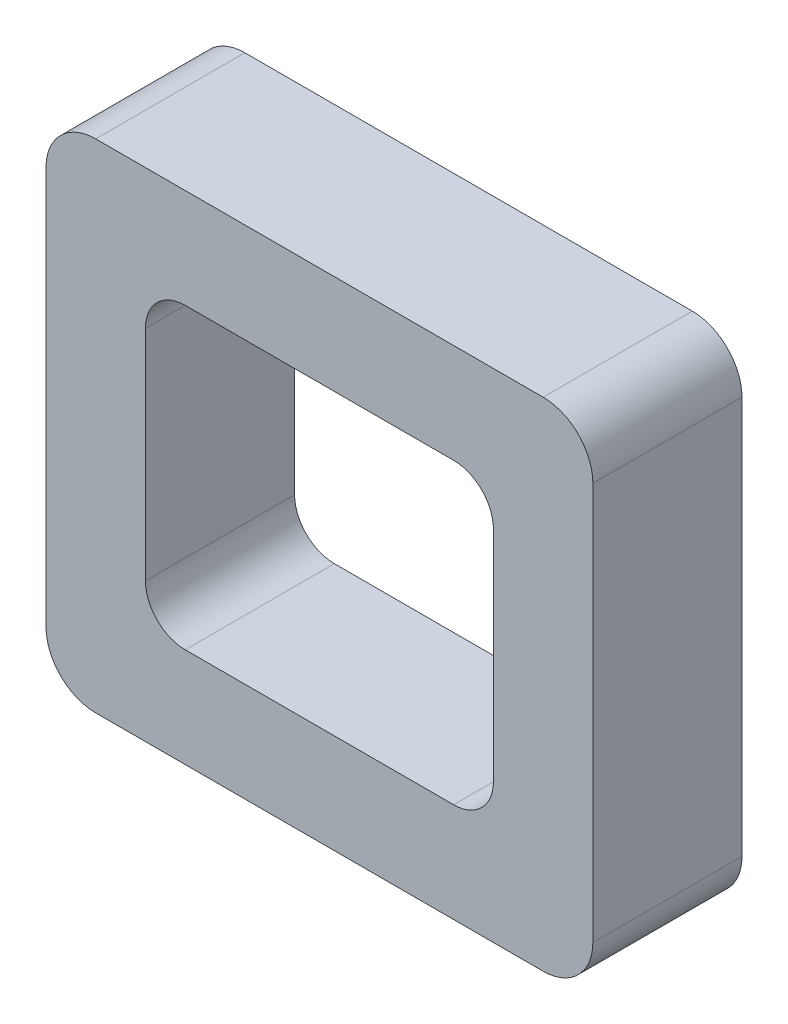
SolidWorks part; units mm, degrees
ref_plane "前视基准面" through (0, 0, 0) normal (0, 0, 1) x (1, 0, 0)
ref_plane "上视基准面" through (0, 0, 0) normal (0, 1, 0) x (1, 0, 0)
ref_plane "右视基准面" through (0, 0, 0) normal (1, 0, 0) x (0, 0, -1)
other "Configuration Table"
sketch "草图1" plane through (0, 0, 0) normal (0, 0, 1) x (1, 0, 0)
  line L1 (-6.4255, 6.8716) -> (2.5745, 6.8716)
  line L2 (-7.4255, 5.8716) -> (-7.4255, -2.1284)
  line L3 (-6.4255, -3.1284) -> (2.5745, -3.1284)
  line L4 (3.5745, 5.8716) -> (3.5745, -2.1284)
  line L5 (-7.4255, 6.8716) -> (3.5745, -3.1284) construction
  line L6 (-7.4255, -3.1284) -> (3.5745, 6.8716) construction
  arc A0 (-7.4255, -2.1284) -> (-6.4255, -3.1284) centre (-6.4255, -2.1284) ccw
  arc A1 (2.5745, -3.1284) -> (3.5745, -2.1284) centre (2.5745, -2.1284) ccw
  arc A2 (2.5745, 6.8716) -> (3.5745, 5.8716) centre (2.5745, 5.8716) cw
  arc A3 (-6.4255, 6.8716) -> (-7.4255, 5.8716) centre (-6.4255, 5.8716) ccw
  point P0 (-1.9255, 1.8716)
  dimension "D3" = 1
  dimension "D1" = 11
  dimension "D2" = 10
extrude "凸台-拉伸1" add sketch "草图1" along normal blind 3
sketch "草图3" plane through (0, 0, 0) normal (0, 0, -1) x (-1, 0, 0)
  line L8 (5.4255, -1.1284) -> (5.4255, 4.8716)
  line L9 (5.4255, 4.8716) -> (-1.5745, 4.8716)
  line L10 (-1.5745, 4.8716) -> (-1.5745, -1.1284)
  line L11 (-1.5745, -1.1284) -> (5.4255, -1.1284)
  line L12 (5.4255, -0.3284) -> (5.4255, 4.0716)
  line L13 (4.6255, 4.8716) -> (-0.7745, 4.8716)
  line L14 (-1.5745, 4.0716) -> (-1.5745, -0.3284)
  line L15 (-0.7745, -1.1284) -> (4.6255, -1.1284)
  arc A4 (-1.5745, -0.3284) -> (-0.7745, -1.1284) centre (-0.7745, -0.3284) ccw
  arc A5 (5.4255, -0.3284) -> (4.6255, -1.1284) centre (4.6255, -0.3284) cw
  arc A6 (5.4255, 4.0716) -> (4.6255, 4.8716) centre (4.6255, 4.0716) ccw
  arc A7 (-0.7745, 4.8716) -> (-1.5745, 4.0716) centre (-0.7745, 4.0716) ccw
  dimension "D2" = 0.8
  dimension "D1" = 2
extrude "切除-拉伸1" cut sketch "草图3" against normal blind 3
